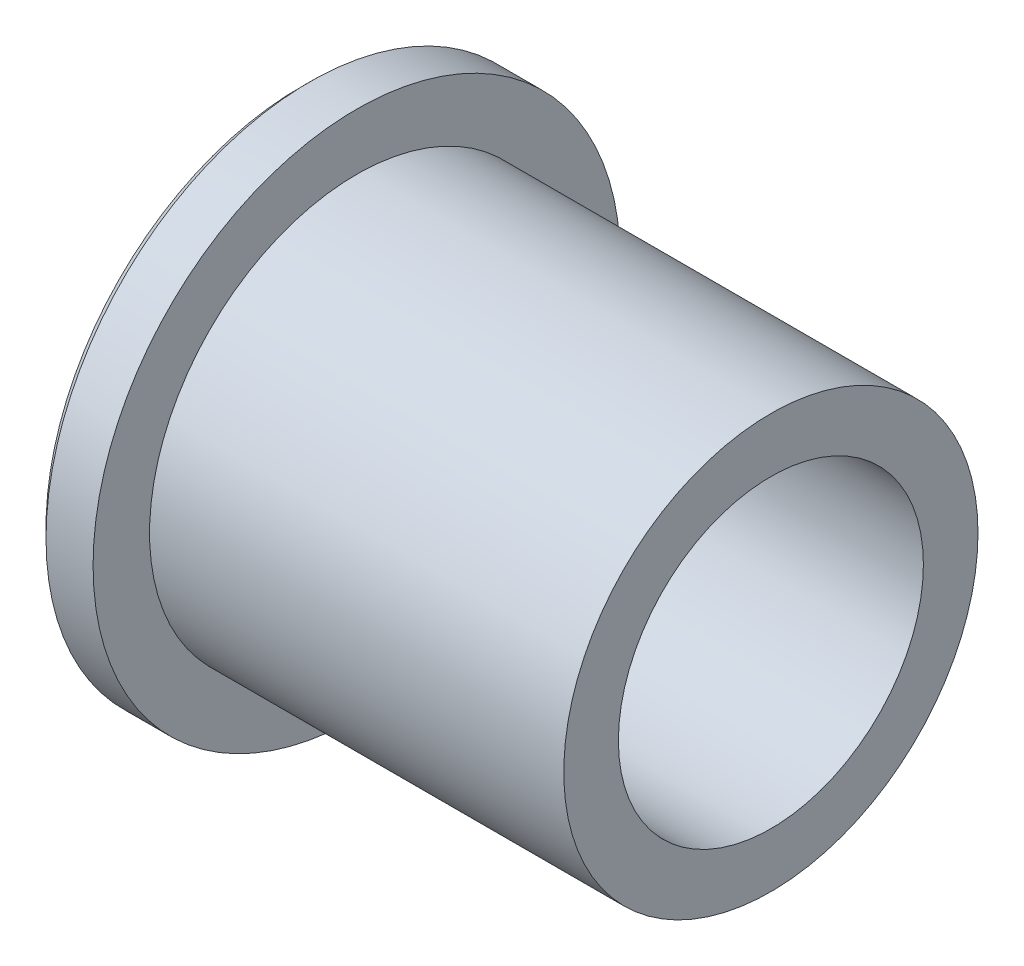
SolidWorks part; units mm, degrees
material "2.1016 (CuSn4)"
ref_plane "Płaszczyzna przednia" through (0, 0, 0) normal (0, 0, 1) x (1, 0, 0)
ref_plane "Płaszczyzna górna" through (0, 0, 0) normal (0, 1, 0) x (1, 0, 0)
ref_plane "Płaszczyzna prawa" through (0, 0, 0) normal (1, 0, 0) x (0, 0, -1)
sketch "Szkic1" plane through (0, 0, 0) normal (1, 0, 0) x (0, 0, -1)
  circle A0 centre (0, 0) radius 14
  circle A1 centre (0, 0) radius 8.1
  dimension "D1" = 28
  dimension "D2" = 16.2
extrude "Dodanie-wyciągnięcie1" add sketch "Szkic1" along normal blind 3
sketch "Szkic2" plane through (3, 0, 0) normal (1, 0, 0) x (0, 0, -1)
  circle A0 centre (0, 0) radius 8.1 construction
  circle A1 centre (0, 0) radius 8.1
  circle A2 centre (0, 0) radius 11
  dimension "D1" = 22
extrude "Dodanie-wyciągnięcie2" add sketch "Szkic2" along normal blind 22
chamfer "Sfazowanie1" distance 0.5 angle 45 1 edges at (0, 0, -14)
